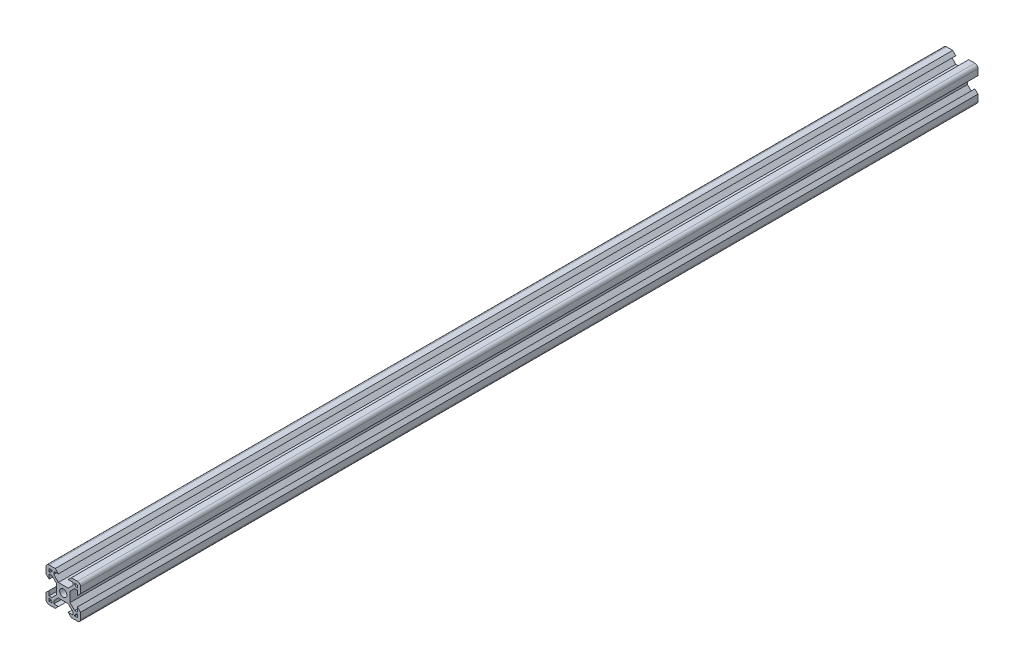
SolidWorks part; units mm, degrees
material "6063-T5"
ref_plane "Plane1" through (0, 0, 0) normal (0, 0, 1) x (1, 0, 0)
ref_plane "Plane2" through (0, 0, 0) normal (0, 1, 0) x (1, 0, 0)
ref_plane "Plane3" through (0, 0, 0) normal (1, 0, 0) x (0, 0, -1)
sketch "Sketch1" plane through (0, 0, 0) normal (0, 0, 1) x (1, 0, 0)
  line L0 (-3.9007, 0) -> (-3.9007, -2.84)
  line L1 (-3.9007, -2.84) -> (-6.56, -5.4993)
  line L2 (-6.56, -5.4993) -> (-8.2, -5.4993)
  line L3 (-8.2, -5.4993) -> (-8.2, -2.84)
  line L4 (-8.2, -2.84) -> (-10, -4.64)
  line L5 (-10, -4.64) -> (-10, -8.2)
  line L6 (0, 0) -> (-17.0509, -17.0509) construction
  line L7 (0, 0) -> (0, -17.0509) construction
  line L8 (0, 0) -> (-30.3777, 0) construction
  line L9 (-4.64, -10) -> (-8.2, -10)
  line L10 (-2.84, -8.2) -> (-4.64, -10)
  line L11 (-5.4993, -8.2) -> (-2.84, -8.2)
  line L12 (-5.4993, -6.56) -> (-5.4993, -8.2)
  line L13 (-2.84, -3.9007) -> (-5.4993, -6.56)
  line L14 (0, -3.9007) -> (-2.84, -3.9007)
  line L15 (-8.2, -8.2) -> (-8.2, -6.5693)
  line L16 (-8.2, -6.5693) -> (-7.63, -6.5693)
  line L17 (-7.63, -6.5693) -> (-6.5693, -7.63)
  line L18 (-6.5693, -7.63) -> (-6.5693, -8.2)
  line L19 (-6.5693, -8.2) -> (-8.2, -8.2)
  line L20 (-3.9007, 0) -> (-3.9007, 2.84)
  line L21 (-3.9007, 2.84) -> (-6.56, 5.4993)
  line L22 (-6.56, 5.4993) -> (-8.2, 5.4993)
  line L23 (-8.2, 5.4993) -> (-8.2, 2.84)
  line L24 (-8.2, 2.84) -> (-10, 4.64)
  line L25 (-10, 4.64) -> (-10, 8.2)
  line L26 (-4.64, 10) -> (-8.2, 10)
  line L27 (-2.84, 8.2) -> (-4.64, 10)
  line L28 (-5.4993, 8.2) -> (-2.84, 8.2)
  line L29 (-5.4993, 6.56) -> (-5.4993, 8.2)
  line L30 (-2.84, 3.9007) -> (-5.4993, 6.56)
  line L31 (0, 3.9007) -> (-2.84, 3.9007)
  line L32 (-8.2, 6.5693) -> (-8.2, 8.2)
  line L33 (-8.2, 8.2) -> (-6.5693, 8.2)
  line L34 (-6.5693, 8.2) -> (-6.5693, 7.63)
  line L35 (-6.5693, 7.63) -> (-7.63, 6.5693)
  line L36 (-7.63, 6.5693) -> (-8.2, 6.5693)
  line L37 (0, 3.9007) -> (2.84, 3.9007)
  line L38 (2.84, 3.9007) -> (5.4993, 6.56)
  line L39 (5.4993, 6.56) -> (5.4993, 8.2)
  line L40 (5.4993, 8.2) -> (2.84, 8.2)
  line L41 (2.84, 8.2) -> (4.64, 10)
  line L42 (4.64, 10) -> (8.2, 10)
  line L43 (10, 4.64) -> (10, 8.2)
  line L44 (8.2, 2.84) -> (10, 4.64)
  line L45 (8.2, 5.4993) -> (8.2, 2.84)
  line L46 (6.56, 5.4993) -> (8.2, 5.4993)
  line L47 (3.9007, 2.84) -> (6.56, 5.4993)
  line L48 (3.9007, 0) -> (3.9007, 2.84)
  line L49 (6.5693, 8.2) -> (8.2, 8.2)
  line L50 (8.2, 8.2) -> (8.2, 6.5693)
  line L51 (8.2, 6.5693) -> (7.63, 6.5693)
  line L52 (7.63, 6.5693) -> (6.5693, 7.63)
  line L53 (6.5693, 7.63) -> (6.5693, 8.2)
  line L54 (3.9007, 0) -> (3.9007, -2.84)
  line L55 (3.9007, -2.84) -> (6.56, -5.4993)
  line L56 (6.56, -5.4993) -> (8.2, -5.4993)
  line L57 (8.2, -5.4993) -> (8.2, -2.84)
  line L58 (8.2, -2.84) -> (10, -4.64)
  line L59 (10, -4.64) -> (10, -8.2)
  line L60 (4.64, -10) -> (8.2, -10)
  line L61 (2.84, -8.2) -> (4.64, -10)
  line L62 (5.4993, -8.2) -> (2.84, -8.2)
  line L63 (5.4993, -6.56) -> (5.4993, -8.2)
  line L64 (2.84, -3.9007) -> (5.4993, -6.56)
  line L65 (0, -3.9007) -> (2.84, -3.9007)
  line L66 (8.2, -6.5693) -> (8.2, -8.2)
  line L67 (8.2, -8.2) -> (6.5693, -8.2)
  line L68 (6.5693, -8.2) -> (6.5693, -7.63)
  line L69 (6.5693, -7.63) -> (7.63, -6.5693)
  line L70 (7.63, -6.5693) -> (8.2, -6.5693)
  circle A0 centre (0, 0) radius 2.1
  arc A1 (-10, -8.2) -> (-8.2, -10) centre (-8.2, -8.2) ccw
  arc A2 (-8.2, 10) -> (-10, 8.2) centre (-8.2, 8.2) ccw
  arc A3 (10, 8.2) -> (8.2, 10) centre (8.2, 8.2) ccw
  arc A4 (8.2, -10) -> (10, -8.2) centre (8.2, -8.2) ccw
  point P23 (-7.0997, -7.0997)
  dimension "D4" = 4.2
  dimension "D1" = 45
  dimension "D2" = 5.68
  dimension "D3" = 1.64
  dimension "D5" = 1.5
  dimension "D6" = 20
  dimension "D7" = 1.8
  dimension "D8" = 1.07
  dimension "D9" = 4
extrude "Extrude1" add sketch "Sketch1" along normal mid plane 519.5
